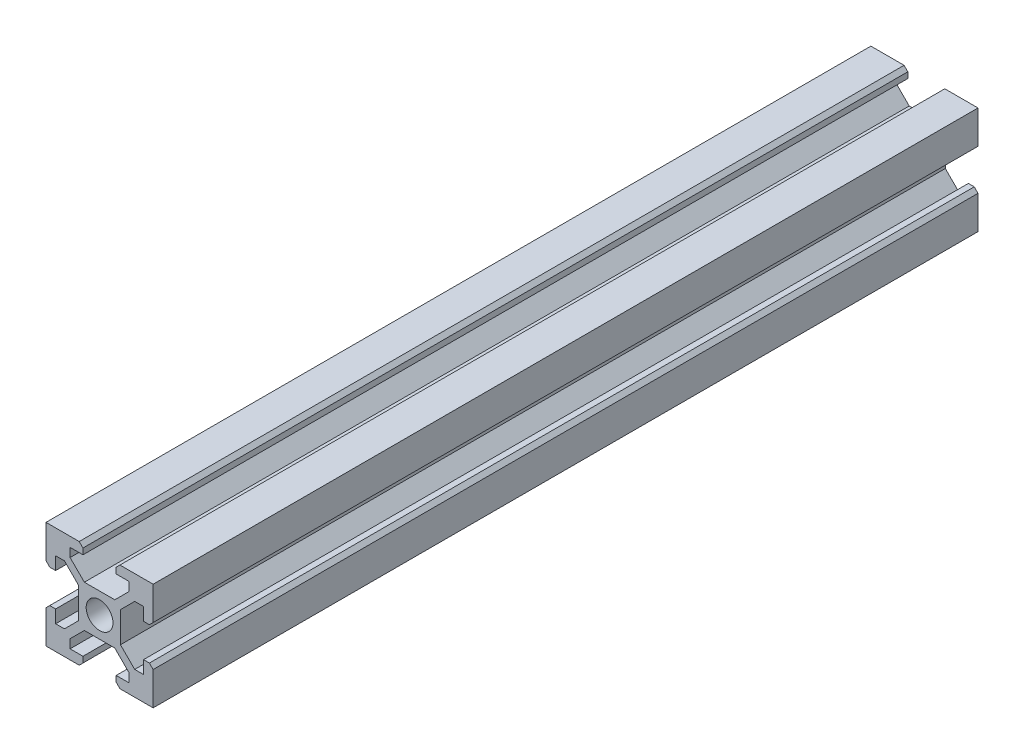
SolidWorks part; units mm, degrees
material "1060 Alloy"
ref_plane "Front Plane" through (0, 0, 0) normal (0, 0, 1) x (1, 0, 0)
ref_plane "Top Plane" through (0, 0, 0) normal (0, 1, 0) x (1, 0, 0)
ref_plane "Right Plane" through (0, 0, 0) normal (1, 0, 0) x (0, 0, -1)
sketch "Sketch1" plane through (0, 0, 0) normal (0, 0, 1) x (1, 0, 0)
  line L0 (3.9, -2.8393) -> (6.5607, -5.5)
  line L1 (-10, 10) -> (10, 10) construction
  line L2 (-10, 10) -> (-10, -10) construction
  line L3 (-10, -10) -> (10, -10) construction
  line L4 (10, 10) -> (10, -10) construction
  line L5 (-10, 10) -> (10, -10) construction
  line L6 (-10, -10) -> (10, 10) construction
  line L7 (-3.9, -3.9) -> (3.9, -3.9) construction
  line L8 (-3.9, -3.9) -> (-3.9, 3.9) construction
  line L9 (-3.9, 3.9) -> (3.9, 3.9) construction
  line L10 (3.9, -3.9) -> (3.9, 3.9) construction
  line L11 (-3.9, -3.9) -> (3.9, 3.9) construction
  line L12 (-3.9, 3.9) -> (3.9, -3.9) construction
  line L13 (-10, 10) -> (-5.5, 10) construction
  line L14 (-10, 10) -> (-10, 5.5) construction
  line L15 (-10, 5.5) -> (-5.5, 5.5) construction
  line L16 (-5.5, 10) -> (-5.5, 5.5) construction
  line L17 (10, 10) -> (5.5, 10) construction
  line L18 (10, 10) -> (10, 5.5) construction
  line L19 (10, 5.5) -> (5.5, 5.5) construction
  line L20 (5.5, 10) -> (5.5, 5.5) construction
  line L21 (-10, -10) -> (-5.5, -10) construction
  line L22 (-10, -10) -> (-10, -5.5) construction
  line L23 (-10, -5.5) -> (-5.5, -5.5) construction
  line L24 (-5.5, -10) -> (-5.5, -5.5) construction
  line L25 (10, -10) -> (5.5, -10) construction
  line L26 (10, -10) -> (10, -5.5) construction
  line L27 (10, -5.5) -> (5.5, -5.5) construction
  line L28 (5.5, -10) -> (5.5, -5.5) construction
  line L29 (2.8393, -3.9) -> (5.5, -6.5607)
  line L30 (-5.5, 6.5607) -> (-2.8393, 3.9)
  line L31 (-6.5607, 5.5) -> (-3.9, 2.8393)
  line L32 (5.5, 6.5607) -> (2.8393, 3.9)
  line L33 (6.5607, 5.5) -> (3.9, 2.8393)
  line L34 (-6.5607, -5.5) -> (-3.9, -2.8393)
  line L35 (-5.5, -6.5607) -> (-2.8393, -3.9)
  line L36 (-2.8393, 3.9) -> (2.8393, 3.9)
  line L37 (-3.9, 2.8393) -> (-3.9, -2.8393)
  line L38 (-2.8393, -3.9) -> (2.8393, -3.9)
  line L39 (3.9, -2.8393) -> (3.9, 2.8393)
  line L40 (5.5, 6.5607) -> (5.5, 8.2007)
  line L41 (5.5, 8.2007) -> (3.1, 8.2007)
  line L42 (3.1, 8.2007) -> (3.1, 9.3)
  line L43 (3.1, 9.3) -> (3.8, 10)
  line L44 (3.8, 10) -> (10, 10)
  line L45 (10, 10) -> (10, 3.8)
  line L46 (10, 3.8) -> (9.3, 3.1)
  line L47 (9.3, 3.1) -> (8.2007, 3.1)
  line L48 (8.2007, 3.1) -> (8.2007, 5.5)
  line L49 (8.2007, 5.5) -> (6.5607, 5.5)
  line L50 (3.1, -8.2007) -> (5.5, -8.2007)
  line L51 (3.1, -9.3) -> (3.1, -8.2007)
  line L52 (3.8, -10) -> (3.1, -9.3)
  line L53 (10, -10) -> (3.8, -10)
  line L54 (10, -3.8) -> (10, -10)
  line L55 (9.3, -3.1) -> (10, -3.8)
  line L56 (8.2007, -3.1) -> (9.3, -3.1)
  line L57 (8.2007, -5.5) -> (8.2007, -3.1)
  line L58 (6.5607, -5.5) -> (8.2007, -5.5)
  line L59 (5.5, -8.2007) -> (5.5, -6.5607)
  line L60 (-8.2007, -3.1) -> (-8.2007, -5.5)
  line L61 (-9.3, -3.1) -> (-8.2007, -3.1)
  line L62 (-10, -3.8) -> (-9.3, -3.1)
  line L63 (-10, -10) -> (-10, -3.8)
  line L64 (-3.8, -10) -> (-10, -10)
  line L65 (-3.1, -9.3) -> (-3.8, -10)
  line L66 (-3.1, -8.2007) -> (-3.1, -9.3)
  line L67 (-5.5, -8.2007) -> (-3.1, -8.2007)
  line L68 (-5.5, -6.5607) -> (-5.5, -8.2007)
  line L69 (-8.2007, -5.5) -> (-6.5607, -5.5)
  line L70 (-3.1, 8.2007) -> (-5.5, 8.2007)
  line L71 (-3.1, 9.3) -> (-3.1, 8.2007)
  line L72 (-3.8, 10) -> (-3.1, 9.3)
  line L73 (-10, 10) -> (-3.8, 10)
  line L74 (-10, 3.8) -> (-10, 10)
  line L75 (-9.3, 3.1) -> (-10, 3.8)
  line L76 (-8.2007, 3.1) -> (-9.3, 3.1)
  line L77 (-8.2007, 5.5) -> (-8.2007, 3.1)
  line L78 (-6.5607, 5.5) -> (-8.2007, 5.5)
  line L79 (-5.5, 8.2007) -> (-5.5, 6.5607)
  circle A0 centre (0, 0) radius 2.5
  point P83 (0, 0)
  dimension "D1" = 5
  dimension "D2" = 20
  dimension "D3" = 7.8
  dimension "D4" = 4.5
  dimension "D5" = 1.5
  dimension "D6" = 0.75
  dimension "D7" = 1.5
  dimension "D8" = 0.75
  dimension "D9" = 1.5
  dimension "D10" = 0.75
  dimension "D11" = 1.5
  dimension "D12" = 0.75
  dimension "D13" = 1.64
  dimension "D14" = 45
  dimension "D15" = 3.1
  dimension "D16" = 6.2
  dimension "D17" = 6.2
  dimension "D18" = 3.1
  dimension "D19" = 4
extrude "Boss-Extrude1" add sketch "Sketch1" along normal mid plane 154 contours L79 L70 L71 L72 L73 L74 L75 L76 L77 L78 L31 L37 L34 L69 L60 L61 L62 L63 L64 L65 L66 L67 L68 L35 L38 L29 L59 L50 L51 L52 L53 L54 L55 L56 L57 L58 L0 L39 L33 L49 L48 L47 L46 L45 L44 L43 L42 L41 L40 L32 L36
